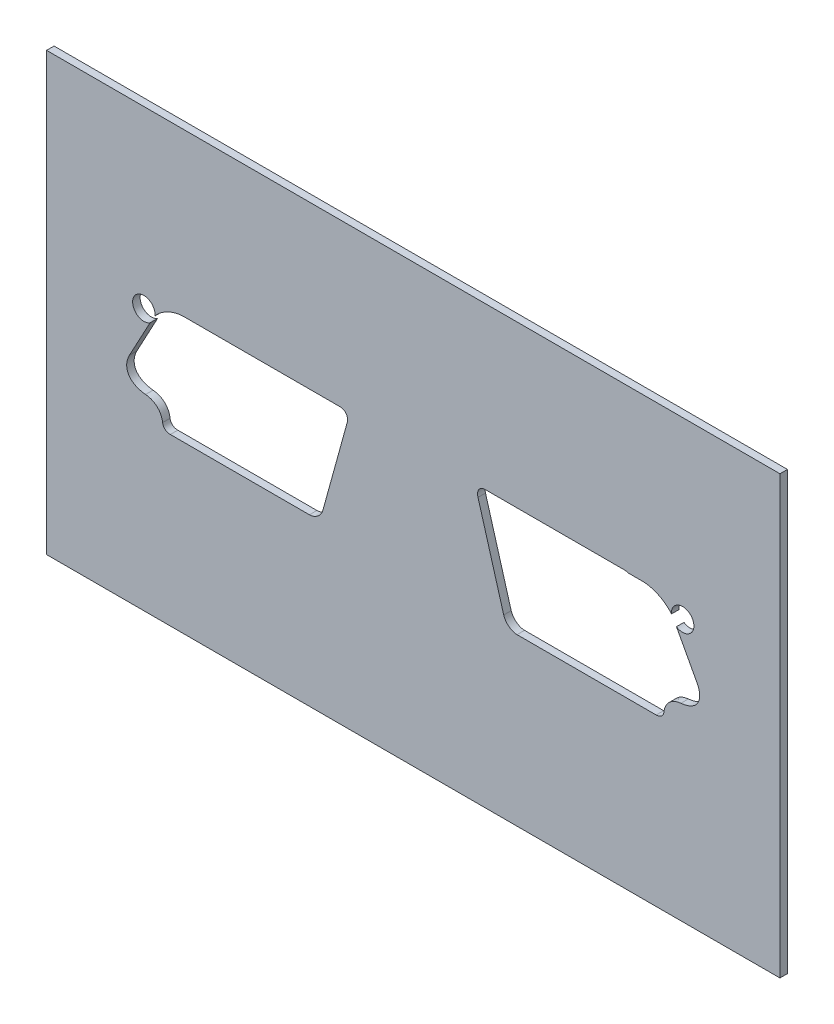
SolidWorks part; units mm, degrees
ref_plane "Спереди" through (0, 0, 0) normal (0, 0, 1) x (1, 0, 0)
ref_plane "Сверху" through (0, 0, 0) normal (0, 1, 0) x (1, 0, 0)
ref_plane "Справа" through (0, 0, 0) normal (1, 0, 0) x (0, 0, -1)
sketch "Эскиз1" plane through (0, 0, 0) normal (0, 0, 1) x (1, 0, 0)
  line L1 (-49, 5.8392) -> (-49, -22.5167)
  line L2 (-49, -22.5167) -> (49, -22.5167)
  line L3 (49, 5.8392) -> (49, -22.5167)
  line L6 (49, 26.4822) -> (49, 5.1962) construction
  line L8 (-49, 5.8392) -> (-49, 15.8392)
  line L9 (-49, 15.8392) -> (49, 15.8392)
  line L10 (49, 5.8392) -> (49, 15.8392)
extrude "Бобышка-Вытянуть1" add sketch "Эскиз1" along normal blind 1
sketch "Эскиз2" plane through (0, 0, 0) normal (0, 0, -1) x (-1, 0, 0)
  line L0 (27.2261, -9.1221) -> (15.7399, -9.1221)
  line L1 (14.9178, -10.1567) -> (17.4421, -18.9309)
  line L2 (19.1226, -20.331) -> (30.8268, -20.331)
  line L3 (31.6433, -19.2954) -> (29.101, -10.4886)
  line L4 (0, 0) -> (0, -19.7017) construction
  line L5 (-31.6433, -19.2954) -> (-29.101, -10.4886)
  line L6 (-19.1226, -20.331) -> (-30.8268, -20.331)
  line L7 (-14.9178, -10.1567) -> (-17.4421, -18.9309)
  line L8 (-27.2261, -9.1221) -> (-15.7399, -9.1221)
  arc A0 (15.7399, -9.1221) -> (14.9178, -10.1567) centre (15.8146, -10.0254) ccw
  arc A1 (17.4421, -18.9309) -> (19.1226, -20.331) centre (19.2232, -18.5017) ccw
  arc A2 (30.8268, -20.331) -> (31.6433, -19.2954) centre (30.7494, -19.4304) ccw
  arc A3 (29.101, -10.4886) -> (27.2261, -9.1221) centre (27.3312, -10.9473) ccw
  arc A4 (-29.101, -10.4886) -> (-27.2261, -9.1221) centre (-27.3312, -10.9473) cw
  arc A5 (-30.8268, -20.331) -> (-31.6433, -19.2954) centre (-30.7494, -19.4304) cw
  arc A6 (-17.4421, -18.9309) -> (-19.1226, -20.331) centre (-19.2232, -18.5017) cw
  arc A7 (-15.7399, -9.1221) -> (-14.9178, -10.1567) centre (-15.8146, -10.0254) cw
extrude "Вырез-Вытянуть4" cut sketch "Эскиз2" against normal through all
sketch "Эскиз4" plane through (0, 0, 0) normal (0, 0, -1) x (-1, 0, 0)
  circle A0 centre (36, -7.525) radius 1.5
  circle A1 centre (-36, -7.525) radius 1.5
extrude "Вырез-Вытянуть5" cut sketch "Эскиз4" against normal through all
sketch "Sketch3" plane through (0, 0, 1) normal (0, 0, 1) x (1, 0, 0)
  line L4 (-35.1709, -8.775) -> (-37.9251, -13.9067)
  line L5 (8.6523, -7.0681) -> (12.0857, -18.9615)
  line L6 (28.2287, -5.6825) -> (9.638, -5.6825)
  line L7 (30.6309, -5.7832) -> (28.7783, -5.7839)
  line L8 (37.9106, -13.8798) -> (35.1709, -8.775)
  line L9 (13.8713, -20.3472) -> (32.462, -20.3472)
  line L10 (8.6523, -7.0681) -> (12.0857, -18.9615)
  line L11 (28.2287, -5.6825) -> (9.638, -5.6825)
  line L12 (30.6309, -5.7832) -> (28.7783, -5.7839)
  line L13 (37.9106, -13.8798) -> (35.1709, -8.775)
  line L14 (13.8713, -20.3472) -> (32.462, -20.3472)
  line L15 (-9.8219, -5.7989) -> (-30.645, -5.807)
  line L16 (-12.0807, -18.9439) -> (-8.8308, -7.1669)
  line L17 (-32.462, -20.3472) -> (-13.8713, -20.3472)
  line L18 (-35.1709, -8.775) -> (-37.9251, -13.9067)
  line L19 (-9.8219, -5.7989) -> (-30.645, -5.807)
  line L20 (-12.0807, -18.9439) -> (-8.8308, -7.1669)
  line L21 (-32.462, -20.3472) -> (-13.8713, -20.3472)
  arc A2 (34.5043, -7.6389) -> (34.5716, -7.9829) centre (36, -7.525) ccw
  arc A3 (34.5716, -7.9829) -> (35.1709, -8.775) centre (36, -7.525) ccw
  arc A4 (34.5043, -7.6389) -> (34.5716, -7.9829) centre (36, -7.525) ccw
  arc A5 (34.5716, -7.9829) -> (35.1709, -8.775) centre (36, -7.525) ccw
  arc A6 (-35.1709, -8.775) -> (-34.5791, -8.0058) centre (-36, -7.525) ccw
  arc A7 (-34.5791, -8.0058) -> (-34.5051, -7.6482) centre (-36, -7.525) ccw
  arc A8 (-35.1709, -8.775) -> (-34.5791, -8.0058) centre (-36, -7.525) ccw
  arc A9 (-34.5791, -8.0058) -> (-34.5051, -7.6482) centre (-36, -7.525) ccw
  ellipse E5 centre (10.038, -7.0681) end of major axis (8.8285, -6.0207) minor radius 1.2 (9.638, -5.6825) -> (8.6523, -7.0681) ccw
  ellipse E6 centre (28.6287, -7.0681) end of major axis (27.4192, -6.0207) minor radius 1.2 (28.7783, -5.7839) -> (28.2287, -5.6825) ccw
  ellipse E7 centre (31.8702, -8.0919) end of major axis (28.7995, -6.6629) minor radius 2 (34.5043, -7.6389) -> (30.6309, -5.7832) ccw
  ellipse E8 centre (32.062, -18.9615) end of major axis (30.8525, -17.9141) minor radius 1.2 (32.462, -20.3472) -> (33.4962, -19.4843) ccw
  ellipse E9 centre (13.4713, -18.9615) end of major axis (12.2618, -17.9141) minor radius 1.2 (12.0857, -18.9615) -> (13.8713, -20.3472) ccw
  ellipse E10 centre (10.038, -7.0681) end of major axis (8.8285, -6.0207) minor radius 1.2 (9.638, -5.6825) -> (8.6523, -7.0681) ccw
  ellipse E11 centre (28.6287, -7.0681) end of major axis (27.4192, -6.0207) minor radius 1.2 (28.7783, -5.7839) -> (28.2287, -5.6825) ccw
  ellipse E12 centre (31.8702, -8.0919) end of major axis (28.7995, -6.6629) minor radius 2 (34.5043, -7.6389) -> (30.6309, -5.7832) ccw
  ellipse E13 centre (32.062, -18.9615) end of major axis (30.8525, -17.9141) minor radius 1.2 (32.462, -20.3472) -> (33.4962, -19.4843) ccw
  ellipse E14 centre (13.4713, -18.9615) end of major axis (12.2618, -17.9141) minor radius 1.2 (12.0857, -18.9615) -> (13.8713, -20.3472) ccw
  ellipse E15 centre (-31.8835, -8.1166) end of major axis (-28.8122, -6.6856) minor radius 2 (-30.645, -5.807) -> (-34.5051, -7.6482) ccw
  ellipse E16 centre (-10.2214, -7.1846) end of major axis (-9.0119, -6.1371) minor radius 1.2 (-8.8308, -7.1669) -> (-9.8219, -5.7989) ccw
  ellipse E17 centre (-13.4713, -18.9615) end of major axis (-12.2618, -17.9141) minor radius 1.2 (-13.8713, -20.3472) -> (-12.0807, -18.9439) ccw
  ellipse E18 centre (-32.062, -18.9615) end of major axis (-30.8525, -17.9141) minor radius 1.2 (-33.4952, -19.4922) -> (-32.462, -20.3472) ccw
  ellipse E19 centre (-37.0781, -20.8189) end of major axis (-34.0544, -18.2003) minor radius 3 (-33.4952, -19.4922) -> (-35.7663, -17.3693) ccw
  ellipse E20 centre (-31.8835, -8.1166) end of major axis (-28.8122, -6.6856) minor radius 2 (-30.645, -5.807) -> (-34.5051, -7.6482) ccw
  ellipse E21 centre (-10.2214, -7.1846) end of major axis (-9.0119, -6.1371) minor radius 1.2 (-8.8308, -7.1669) -> (-9.8219, -5.7989) ccw
  ellipse E22 centre (-13.4713, -18.9615) end of major axis (-12.2618, -17.9141) minor radius 1.2 (-13.8713, -20.3472) -> (-12.0807, -18.9439) ccw
  ellipse E23 centre (-32.062, -18.9615) end of major axis (-30.8525, -17.9141) minor radius 1.2 (-33.4952, -19.4922) -> (-32.462, -20.3472) ccw
  ellipse E24 centre (-37.0781, -20.8189) end of major axis (-34.0544, -18.2003) minor radius 3 (-33.4952, -19.4922) -> (-35.7663, -17.3693) ccw
  spline S1 degree 3 poles (-3612.3196, -1806.8838) (141.1066, -20.6987) (-32.5994, 3.1691) (-38.2359, -14.6873) (-38.2784, -14.8959) (-38.2974, -15.2122) (-38.2963, -15.3175) (-38.2774, -15.5276) (-38.2593, -15.6333) (-38.206, -15.8369) (-38.1708, -15.9356) (-38.0829, -16.1267) (-38.0295, -16.2198) (-37.8491, -16.4795) (-37.6989, -16.6311) (-37.3628, -16.8865) (-37.1797, -16.9895) (-17.2345, -25.642) (53.9483, 176.5986) (-943.5135, -3912.4154) knots -10.923116 -10.923116 -10.923116 -10.923116 0.125 0.125 0.25 0.25 0.3125 0.3125 0.375 0.375 0.4375 0.4375 0.5 0.5 0.625 0.625 0.75 0.75 13.437928 13.437928 13.437928 13.437928 only from (-37.9251, -13.9067) to (-35.7663, -17.3693)
  spline S2 degree 3 poles (2061.9964, -3465.9377) (-69.0178, 170.9177) (17.3944, -25.618) (37.1704, -16.959) (37.355, -16.8543) (37.6875, -16.5998) (37.8383, -16.4466) (38.0766, -16.1015) (38.1662, -15.9056) (38.2715, -15.4997) (38.2888, -15.2855) (38.2633, -14.8675) (38.2207, -14.6579) (31.82, 5.5764) (-180.6478, -51.2528) (3762.9572, 1441.6708) knots -12.455389 -12.455389 -12.455389 -12.455389 0.25 0.25 0.375 0.375 0.5 0.5 0.625 0.625 0.75 0.75 0.875 0.875 13.404708 13.404708 13.404708 13.404708 only from (35.7615, -17.3421) to (37.9106, -13.8798)
  spline S3 degree 3 poles (203.5774, 3973.3026) (187.7595, -140.5035) (26.2256, -34.1242) (33.8533, -18.4172) (34.0253, -18.1839) (34.4362, -17.8036) (34.6819, -17.6499) (51.4194, -10.709) (148.6693, -173.0193) (-3938.8197, 407.6381) knots -15.007963 -15.007963 -15.007963 -15.007963 0.25 0.25 0.5 0.5 0.75 0.75 16.651429 16.651429 16.651429 16.651429 only from (33.4962, -19.4843) to (35.7615, -17.3421)
  spline S4 degree 3 poles (35.7615, -17.3421) (36.1812, -17.3014) (36.5924, -17.2121) (37.1704, -16.959) (37.355, -16.8543) (37.6875, -16.5998) (37.8383, -16.4466) (38.0766, -16.1015) (38.1662, -15.9056) (38.2715, -15.4997) (38.2888, -15.2855) (38.2633, -14.8675) (38.2207, -14.6579) (38.0943, -14.2582) (38.0105, -14.066) (37.9106, -13.8798) knots 0 0 0 0 0.25 0.25 0.375 0.375 0.5 0.5 0.625 0.625 0.75 0.75 0.875 0.875 1 1 1 1
  spline S5 degree 3 poles (33.4962, -19.4843) (33.5297, -19.2012) (33.6073, -18.9236) (33.8533, -18.4172) (34.0253, -18.1839) (34.4362, -17.8036) (34.6819, -17.6499) (35.2, -17.4351) (35.4791, -17.3694) (35.7615, -17.3421) knots 0 0 0 0 0.25 0.25 0.5 0.5 0.75 0.75 1 1 1 1
  spline S6 degree 3 poles (-37.9251, -13.9067) (-38.0252, -14.0933) (-38.1098, -14.2878) (-38.2359, -14.6873) (-38.2784, -14.8959) (-38.2974, -15.2122) (-38.2963, -15.3175) (-38.2774, -15.5276) (-38.2593, -15.6333) (-38.206, -15.8369) (-38.1708, -15.9356) (-38.0829, -16.1267) (-38.0295, -16.2198) (-37.8491, -16.4795) (-37.6989, -16.6311) (-37.3628, -16.8865) (-37.1797, -16.9895) (-36.5959, -17.2427) (-36.1868, -17.3297) (-35.7663, -17.3693) knots 0 0 0 0 0.125 0.125 0.25 0.25 0.3125 0.3125 0.375 0.375 0.4375 0.4375 0.5 0.5 0.625 0.625 0.75 0.75 1 1 1 1
  dimension "D1" = 0
  dimension "D2" = 0
extrude "Cut-Extrude1" cut sketch "Sketch3" against normal up to surface (1 mm away) up to face at (-37.5, -7.525, 0)
sketch "Sketch4" plane through (0, 0, 1) normal (0, 0, 1) x (1, 0, 0)
  line L0 (49, -22.5167) -> (49, 15.8392) construction
  line L1 (-49, -22.5167) -> (49, -22.5167)
  line L2 (-49, -22.5167) -> (-49, -42.5167)
  line L3 (-49, -42.5167) -> (49, -42.5167)
  line L4 (49, -22.5167) -> (49, -42.5167)
  dimension "D1" = 0
  dimension "D2" = 20
extrude "Boss-Extrude1" add sketch "Sketch4" against normal blind 1
